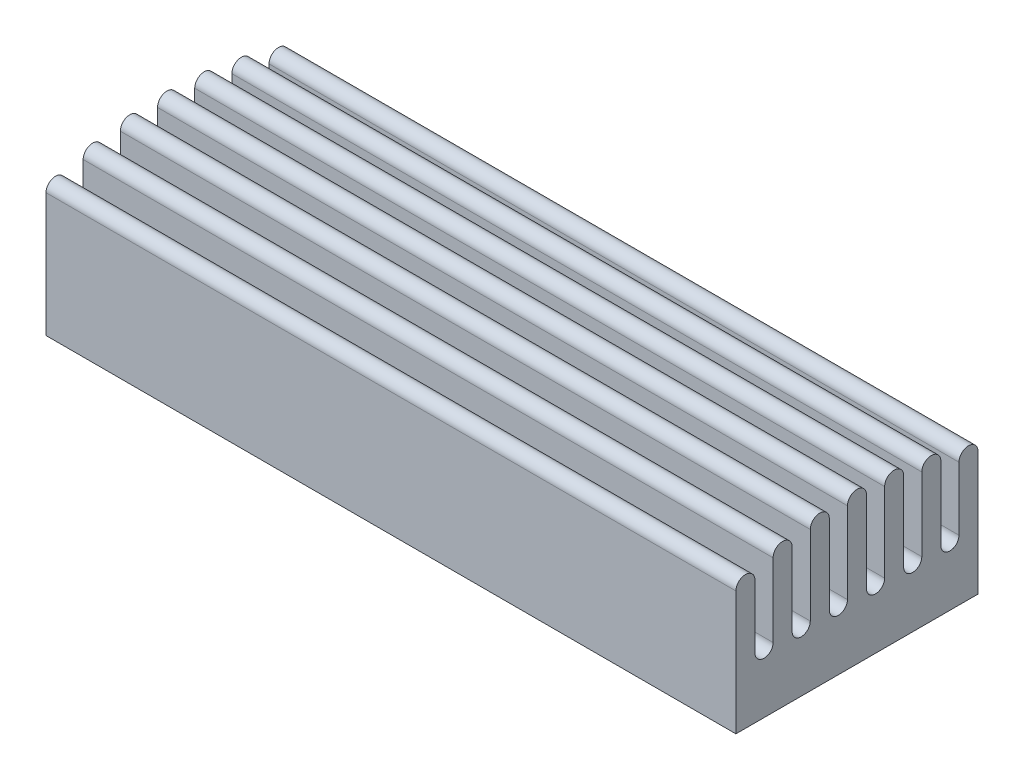
SolidWorks part; units mm, degrees
ref_plane "Front Plane" through (0, 0, 0) normal (0, 0, 1) x (1, 0, 0)
ref_plane "Top Plane" through (0, 0, 0) normal (0, 1, 0) x (1, 0, 0)
ref_plane "Right Plane" through (0, 0, 0) normal (1, 0, 0) x (0, 0, -1)
sketch "Sketch2" plane through (0, 0, 0) normal (0, 1, 0) x (1, 0, 0)
  line L1 (-28.5, 10) -> (28.5, 10)
  line L2 (-28.5, 10) -> (-28.5, -10)
  line L3 (-28.5, -10) -> (28.5, -10)
  line L4 (28.5, 10) -> (28.5, -10)
  line L5 (-28.5, 10) -> (28.5, -10) construction
  line L6 (-28.5, -10) -> (28.5, 10) construction
  point P0 (0, 0)
  dimension "D1" = 57
  dimension "D2" = 20
extrude "Boss-Extrude1" add sketch "Sketch2" along normal blind 12.5
sketch "Sketch3" plane through (28.5, 0, 0) normal (1, 0, 0) x (0, 0, -1)
  line L0 (-10, 12.5) -> (-10, 10.2231)
  line L1 (-10, 12.5) -> (-10, 0) construction
  line L2 (-8.4286, 10.2231) -> (-8.4286, 5)
  line L3 (-6.9286, 5) -> (-6.9286, 11.0612)
  line L4 (-5.3571, 11.0612) -> (-5.3571, 5)
  line L5 (-3.8571, 5) -> (-3.8571, 11.5524)
  line L6 (-2.2857, 11.5524) -> (-2.2857, 5)
  line L7 (-0.7857, 5) -> (-0.7857, 11.7143)
  line L8 (-10, 12.5) -> (10, 12.5) construction
  line L9 (-10, 0) -> (10, 0) construction
  line L10 (10, 12.5) -> (10, 0) construction
  line L11 (-10, 12.5) -> (0, 12.5)
  arc A0 (-10, 10.2231) -> (-8.4286, 10.2231) centre (-9.2143, 10.2231) cw
  arc A1 (-8.4286, 5) -> (-6.9286, 5) centre (-7.6786, 5) ccw
  arc A2 (-6.9286, 11.0612) -> (-5.3571, 11.0612) centre (-6.1429, 11.0612) cw
  arc A3 (-5.3571, 5) -> (-3.8571, 5) centre (-4.6071, 5) ccw
  arc A4 (-3.8571, 11.5524) -> (-2.2857, 11.5524) centre (-3.0714, 11.5524) cw
  arc A5 (-2.2857, 5) -> (-0.7857, 5) centre (-1.5357, 5) ccw
  arc A6 (-0.7857, 11.7143) -> (0, 12.5) centre (0, 11.7143) cw
  arc A7 (-10, 10.7843) -> (10, 10.7843) centre (0, -17.5) cw construction
  point P26 (0, 12.5)
  dimension "D3" = 30
  dimension "D1" = 1.5
  dimension "D2" = 5
extrude "Cut-Extrude1" cut sketch "Sketch3" against normal up to surface (57 mm away) up to face at (-28.5, 6.25, 0)
mirror "Mirror1" about plane through (0, 0, 0) normal (0, 0, 1) of "Cut-Extrude1"
